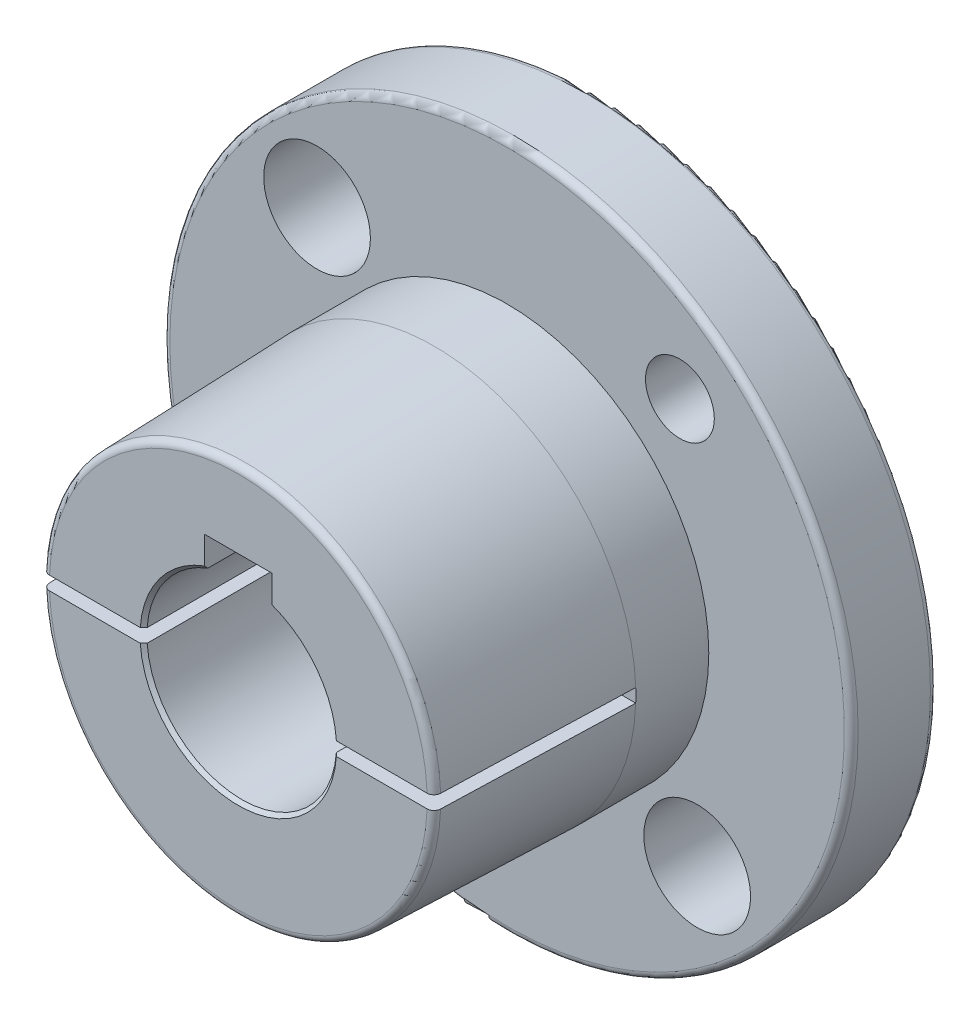
SolidWorks part; units mm, degrees
material "INOX AISI 304"
ref_plane "Front Plane" through (0, 0, 0) normal (0, 0, 1) x (1, 0, 0)
ref_plane "Top Plane" through (0, 0, 0) normal (0, 1, 0) x (1, 0, 0)
ref_plane "Right Plane" through (0, 0, 0) normal (1, 0, 0) x (0, 0, -1)
sketch "Sketch1" plane through (0, 0, 0) normal (1, 0, 0) x (0, 0, -1)
  line L0 (-13.0937, 7) -> (-13.0937, 14.4328)
  line L1 (-13.0937, 14.4328) -> (1.3589, 14.8844)
  line L2 (1.3589, 14.8844) -> (6.7437, 14.8844)
  line L3 (6.7437, 14.8844) -> (6.7437, 25.4)
  line L4 (6.7437, 25.4) -> (13.0937, 25.4)
  line L5 (13.0937, 25.4) -> (13.0937, 7)
  line L6 (13.0937, 7) -> (-13.0937, 7)
  line L7 (-13.0937, 0) -> (13.0937, 0) construction
  line L8 (55, 0) -> (-55, 0) construction
  line L9 (0, 55) -> (0, -55) construction
  point P12 (0, 7)
  dimension "D" = 26.1874
  dimension "D4" = 1.79
  dimension "E" = 6.35
  dimension "C" = 5.3848
  dimension "B" = 29.7688
  dimension "A" = 50.8
  dimension "Bore diameter" = 14
revolve "Revolve1" add sketch "Sketch1" angle 360 about L7
fillet "Fillet1" radius 0.508 2 edges at (25.4, 0, -6.7437) (25.4, 0, -13.0937)
fillet "Fillet2" radius 0.508 1 edges at (14.4328, 0, 13.0937)
chamfer "Chamfer1" distance 0.254 angle 45 2 edges at (7, 0, -13.0937) (7, 0, 13.0937)
sketch "Sketch19" plane through (0, 0, -6.7437) normal (0, 0, 1) x (1, 0, 0)
  line L0 (0, 0) -> (0, 19.8374) construction
  line L1 (12.7512, 15.1963) -> (0, 0) construction
  line L2 (0, 0) -> (-12.7512, -15.1963) construction
  circle A0 centre (0, 0) radius 19.8374 construction
  circle A1 centre (12.7512, 15.1963) radius 2.54
  circle A2 centre (-12.7512, -15.1963) radius 2.54
  dimension "Threaded circle diameter" = 39.6748
  dimension "D2" = 5.08
  dimension "D3" = 40
  dimension "D4" = 220
extrude "Threaded holes 1" cut sketch "Sketch19" against normal through all
cosmetic thread "Cosmetic Thread3" parameters "D2"=5.09
cosmetic thread "Cosmetic Thread4" parameters "D2"=5.09
sketch "Sketch22" plane through (0, 0, -6.7437) normal (0, 0, 1) x (1, 0, 0)
  line L0 (-14.0272, 14.0272) -> (0, 0) construction
  line L1 (0, 0) -> (0, 19.8374) construction
  circle A0 centre (0, 0) radius 19.8374 construction
  circle A1 centre (-14.0272, 14.0272) radius 3.937
  dimension "D1" = 45
  dimension "Clearance diameter" = 39.6748
  dimension "Clearance hole diam" = 7.874
extrude "Clearance holes" cut sketch "Sketch22" against normal through all
pattern_circular "Clearance holes CirPattern" count 2 over 360 about axis through (0, 0, 0) along (0, 0, 1) of "Clearance holes"
ref_plane "Plane1" through (0, 0, -1.3589) normal (0, 0, 1) x (1, 0, 0)
sketch "Sketch23" plane through (0, 0, 13.0937) normal (0, 0, 1) x (1, 0, 0)
  line L7 (-2.5, 8.8383) -> (2.5, 8.8383)
  line L8 (-2.5, 8.8383) -> (-2.5, 6.5383)
  line L9 (-2.5, 6.5383) -> (2.5, 6.5383)
  line L10 (2.5, 8.8383) -> (2.5, 6.5383)
  line L11 (-2.5, 8.8383) -> (2.5, 6.5383) construction
  line L12 (-2.5, 6.5383) -> (2.5, 8.8383) construction
  circle A0 centre (0, 0) radius 7 construction
  point P0 (0, 0)
  point P1 (0, 8.8383)
  point P7 (1.9181, 5.0165)
  point P12 (0, 7.6883)
  point P13 (0, 0)
  dimension "D3" = 5
  dimension "D4" = 2.3
extrude "Cut-Extrude1" cut sketch "Sketch23" along a picked direction on the side against the normal through all
sketch "Sketch24" plane through (0, 0, 13.0937) normal (0, 0, 1) x (1, 0, 0)
  line L1 (-14.8844, 0.5) -> (14.8844, 0.5)
  line L2 (-14.8844, 0.5) -> (-14.8844, -0.5)
  line L3 (-14.8844, -0.5) -> (14.8844, -0.5)
  line L4 (14.8844, 0.5) -> (14.8844, -0.5)
  line L5 (-14.8844, 0.5) -> (14.8844, -0.5) construction
  line L6 (-14.8844, -0.5) -> (14.8844, 0.5) construction
  circle A1 centre (0, 0) radius 14.8844 construction
  point P4 (0, 0)
  point P8 (0, 0)
  dimension "D1" = 1
extrude "Cut-Extrude2" cut sketch "Sketch24" against normal up to surface (14.4526 mm away)
equation "\"D1@Sketch12\"=\"D2@Sketch10\""
equation "\"D1@Plane2\"=\"A@Sketch1\"/2"
equation "\"D1@Sketch13\"=\"E@Sketch1\"/2"
equation "\"D2@Cosmetic Thread3\"=\"D2@Sketch19\"+.01"
equation "\"D2@Cosmetic Thread4\"=\"D2@Cosmetic Thread3\""
equation "\"D2@Sketch21\"=\"D2@Sketch19\""
equation "\"D1@Sketch21\"=\"Threaded circle diameter@Sketch19\""
equation "\"D2\" = \"D2@Cosmetic Thread3\""
equation "\"D1@Plane3\"=\"D@Sketch1\"/2"
equation "\"D1@Plane4\"=\"D@Sketch1\"/2"
equation "\"D2\" = \"Thru Hole Dia.@Sketch15\" + .1"
